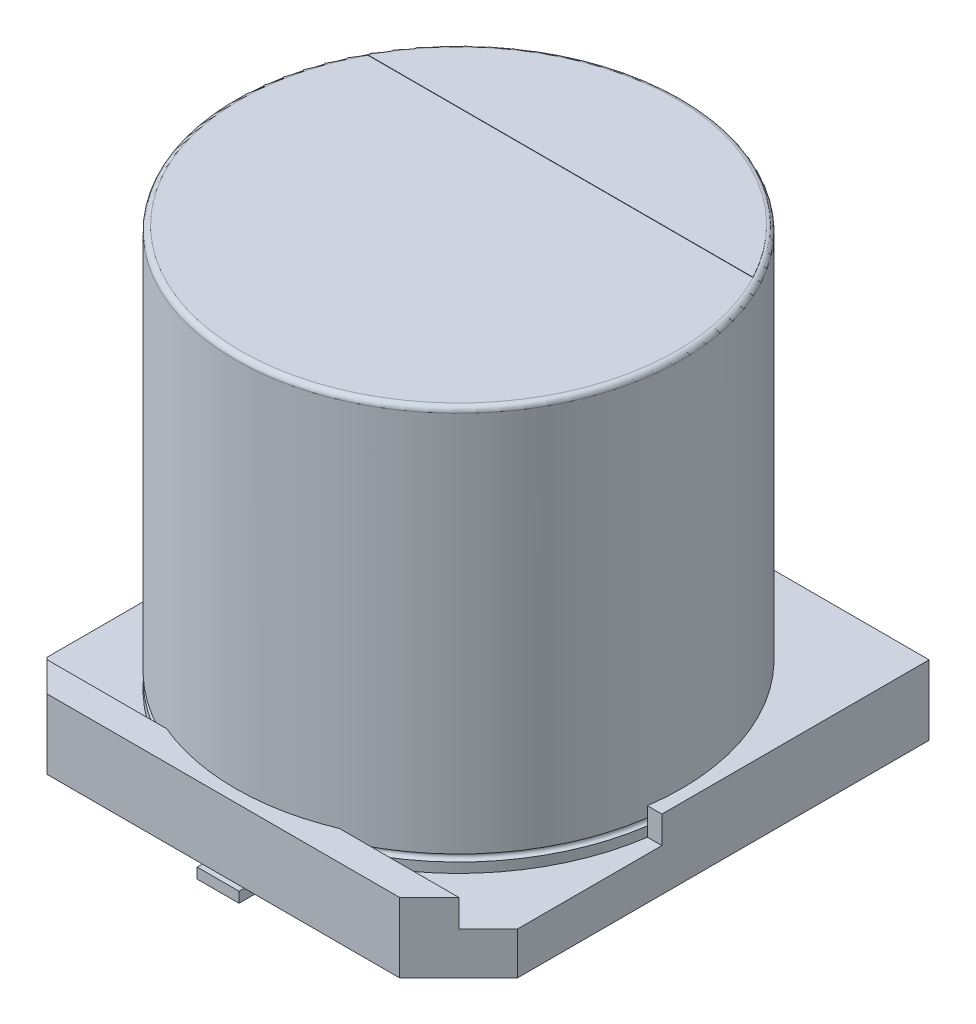
SolidWorks part; units mm, degrees
ref_plane "Front Plane" through (0, 0, 0) normal (0, 0, 1) x (1, 0, 0)
ref_plane "Top Plane" through (0, 0, 0) normal (0, 1, 0) x (1, 0, 0)
ref_plane "Right Plane" through (0, 0, 0) normal (1, 0, 0) x (0, 0, -1)
sketch "Sketch1" plane through (0, 0, 0) normal (0, 1, 0) x (1, 0, 0)
  line L0 (-6.75, 6.75) -> (6.75, 6.75)
  line L1 (6.75, 6.75) -> (6.75, -5.0618)
  line L2 (6.75, -5.0618) -> (5.0618, -6.75)
  line L3 (5.0618, -6.75) -> (-5.0618, -6.75)
  line L4 (-5.0618, -6.75) -> (-6.75, -5.0618)
  line L5 (-6.75, -5.0618) -> (-6.75, 6.75)
  line L6 (0, 5.1629) -> (0, -6.366) construction
  line L7 (-5.4826, 0) -> (5.3839, 0) construction
  point P12 (0, -6.75)
  dimension "D1" = 13.5
  dimension "D2" = 13.5
extrude "Boss-Extrude1" add sketch "Sketch1" along normal blind 2
sketch "Sketch2" plane through (0, 2, 0) normal (0, 1, 0) x (1, 0, 0)
  circle A0 centre (0, 0) radius 6.4
  dimension "D1" = 12.8
extrude "Cut-Extrude1" cut sketch "Sketch2" against normal blind 1
sketch "Sketch8" plane through (-6.75, 0, 0) normal (-1, 0, 0) x (0, 0, 1)
  line L1 (0.9165, 1.2174) -> (5.9, 1.2174)
  line L2 (0.9165, 1.2174) -> (0.9165, 2.8185)
  line L3 (0.9165, 2.8185) -> (5.9, 2.8185)
  line L4 (5.9, 1.2174) -> (5.9, 2.8185)
extrude "Cut-Extrude4" cut sketch "Sketch8" against normal up to surface (13.5 mm away) up to face at (6.75, 1, -0.8441)
sketch "Sketch5" plane through (0, 0, 0) normal (0, 0, 1) x (1, 0, 0)
  line L0 (0, 0) -> (0, 10.407) construction
  line L2 (0, 0) -> (-6.4, 0)
  line L3 (-6.4, 0) -> (-6.4, 1.5)
  line L4 (-6.4, 1.7) -> (-6.4, 12.65)
  line L5 (-6.25, 12.8) -> (0, 12.8)
  line L6 (0, 12.8) -> (0, 0)
  arc A0 (-6.4, 1.5) -> (-6.4, 1.7) centre (-6.4, 1.6) ccw
  arc A1 (-6.4, 12.65) -> (-6.25, 12.8) centre (-6.25, 12.65) cw
  point P2 (0, 0)
  dimension "D1" = 0.1
  dimension "D4" = 0.15
  dimension "D2" = 12.8
  dimension "D3" = 1.5
  dimension "D5" = 6.25
revolve "Revolve1" add sketch "Sketch5" angle 360 about L6
sketch "Sketch6" plane through (0, 12.8, 0) normal (0, 1, 0) x (1, 0, 0)
  line L0 (-5.5254, 2.9211) -> (5.5254, 2.9211)
  circle A0 centre (0, 0) radius 6.25 construction
  arc A1 (5.5254, 2.9211) -> (-5.5254, 2.9211) centre (0, 0) ccw
extrude "Boss-Extrude4" add sketch "Sketch6" along normal blind 0.01
sketch "Sketch9" plane through (0, 0, 0) normal (0, -1, 0) x (1, 0, 0)
  line L0 (0, 4.3805) -> (0, -0.5544) construction
  line L1 (4.5693, 0) -> (-4.8861, 0) construction
  line L2 (0.6, -6.9) -> (-0.6, -6.9)
  line L3 (0.6, 2.2) -> (-0.6, 2.2)
  line L4 (0.6, 2.2) -> (0.6, 6.9)
  line L5 (0.6, 6.9) -> (-0.6, 6.9)
  line L6 (-0.6, 2.2) -> (-0.6, 6.9)
  line L7 (0.6, 2.2) -> (-0.6, 6.9) construction
  line L8 (0.6, 6.9) -> (-0.6, 2.2) construction
  line L9 (-0.6, -2.2) -> (-0.6, -6.9)
  line L10 (0.6, -2.2) -> (-0.6, -2.2)
  line L11 (0.6, -2.2) -> (0.6, -6.9)
  point P5 (0, 4.55)
  dimension "D1" = 2.2
  dimension "D2" = 4.7
  dimension "D3" = 1.2
extrude "Boss-Extrude5" add sketch "Sketch9" along normal blind 0.3
